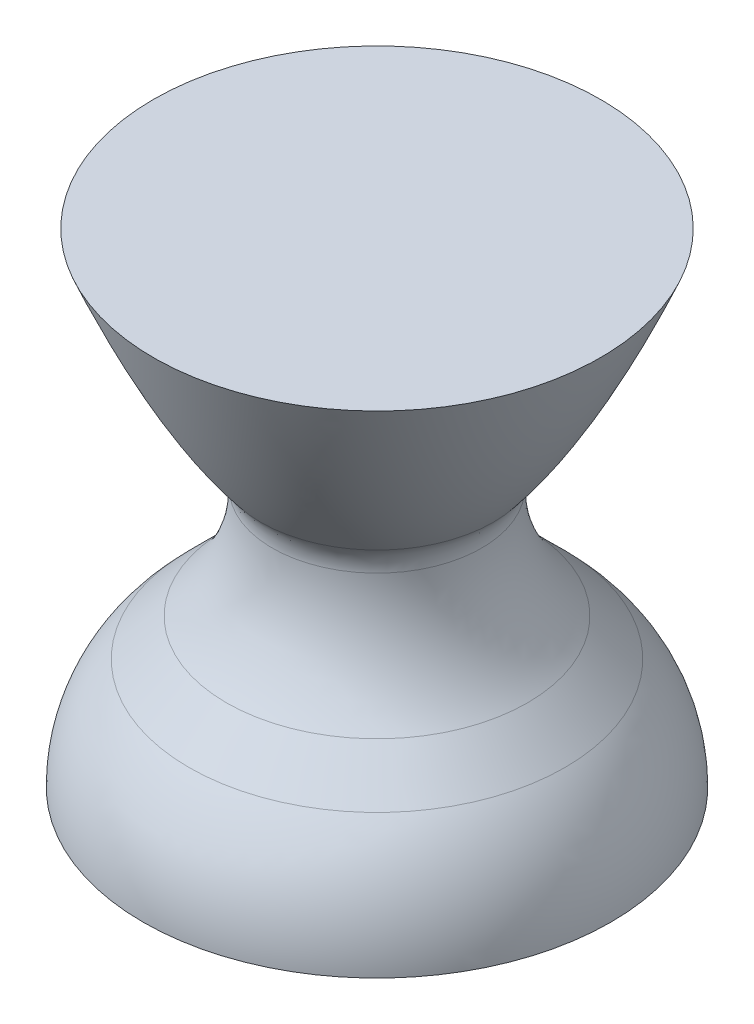
SolidWorks part; units mm, degrees
ref_plane "Front Plane" through (0, 0, 0) normal (0, 0, 1) x (1, 0, 0)
ref_plane "Top Plane" through (0, 0, 0) normal (0, 1, 0) x (1, 0, 0)
ref_plane "Right Plane" through (0, 0, 0) normal (1, 0, 0) x (0, 0, -1)
sketch "Sketch1" plane through (0, 0, 0) normal (0, 0, 1) x (1, 0, 0)
  line L0 (0, 61.1625) -> (0, -71.9343) construction
  line L1 (53.8816, -59.7274) -> (0, -59.7274)
  line L2 (51.5099, 51.7205) -> (0, 51.7205)
  line L3 (0, 51.7205) -> (0, -59.7274)
  spline S0 degree 2 poles (26.7954, 6.5095) (39.1527, 21.9803) (51.5099, 51.7205) knots 0 0 0 1 1 1 construction
  spline S1 degree 2 poles (26.7954, 6.5095) (39.1527, 21.9803) (51.5099, 51.7205) knots 0 0 0 1 1 1
  spline S2 degree 4 poles (24.127, -0.7178) (24.1261, -0.7017) (24.1244, -0.6737) (24.1211, -0.6545) (24.1152, -0.5165) (24.106, -0.4368) (24.0995, -0.1065) (24.0981, 0.0019) (24.1021, 0.2679) (24.1086, 0.4273) (24.1207, 0.647) (24.1416, 0.9017) (24.1753, 1.2028) (24.2266, 1.5423) (24.2907, 1.8813) (24.3673, 2.2166) (24.4564, 2.5495) (24.5579, 2.8784) (24.6717, 3.2036) (24.7973, 3.5239) (24.9354, 3.8399) (25.0842, 4.1496) (25.2461, 4.4551) (25.4166, 4.7516) (25.6026, 5.046) (25.7919, 5.3258) (26.0045, 5.611) (26.179, 5.8332) (26.3665, 6.0502) (26.5047, 6.2089) (26.7571, 6.4729) (26.8371, 6.5527) (27.1017, 6.8061) (27.1882, 6.8784) (27.2855, 6.9668) (27.3039, 6.9805) (27.3265, 7.0005) knots 0 0 0 0 0 0.005192 0.010384 0.020768 0.041536 0.082569 0.102427 0.122284 0.142142 0.162 0.201716 0.241431 0.281147 0.320863 0.360578 0.400294 0.44001 0.479725 0.519441 0.559156 0.598872 0.638588 0.678303 0.718019 0.757735 0.79745 0.837166 0.857024 0.876882 0.916597 0.958047 0.979024 0.989512 1 1 1 1 1 construction
  spline S3 degree 4 poles (24.0992, 0.0003) (24.0992, 0.0362) (24.0997, 0.1104) (24.1021, 0.2679) (24.1086, 0.4273) (24.1207, 0.647) (24.1416, 0.9017) (24.1753, 1.2028) (24.2266, 1.5423) (24.2907, 1.8813) (24.3673, 2.2166) (24.4564, 2.5495) (24.5579, 2.8784) (24.6717, 3.2036) (24.7973, 3.5239) (24.9354, 3.8399) (25.0842, 4.1496) (25.2461, 4.4551) (25.4166, 4.7516) (25.6026, 5.046) (25.7919, 5.3258) (26.0045, 5.611) (26.179, 5.8332) (26.3665, 6.0502) (26.5047, 6.2089) (26.6706, 6.3824) (26.7446, 6.4588) (26.7954, 6.5095) knots 0.082569 0.082569 0.082569 0.082569 0.082569 0.102427 0.122284 0.142142 0.162 0.201716 0.241431 0.281147 0.320863 0.360578 0.400294 0.44001 0.479725 0.519441 0.559156 0.598872 0.638588 0.678303 0.718019 0.757735 0.79745 0.837166 0.857024 0.876882 0.916597 0.916597 0.916597 0.916597 0.916597
  spline S4 degree 4 poles (24.2083, 2.8081) (24.2015, 2.7167) (24.1883, 2.5519) (24.1643, 2.1755) (24.1353, 1.6882) (24.115, 1.1019) (24.1031, 0.6557) (24.0989, 0.1105) (24.0989, -0.0998) (24.1021, -0.5429) (24.1084, -0.8239) (24.1179, -1.1945) (24.1305, -1.5132) (24.1463, -1.8617) (24.1653, -2.1934) (24.1929, -2.6178) (24.2324, -3.1218) (24.3034, -3.8797) (24.4232, -4.8862) (24.5996, -6.0564) (24.851, -7.3849) (25.1519, -8.7033) (25.5019, -10.0094) (25.9005, -11.3015) (26.3471, -12.5778) (26.8411, -13.8366) (27.3818, -15.0759) (27.9686, -16.2943) (28.6003, -17.4897) (29.2767, -18.661) (29.9956, -19.8055) (30.7581, -20.9236) (31.4593, -21.8741) (32.0889, -22.6732) (32.6242, -23.3201) (33.0724, -23.8397) (33.5086, -24.3295) (33.9359, -24.7882) (34.2457, -25.1136) (34.6122, -25.4858) (34.7662, -25.6397) (35.151, -26.0186) (35.4777, -26.3285) (35.9051, -26.7271) (36.2397, -27.0241) (36.5193, -27.2706) (36.6466, -27.3797) (36.7149, -27.4386) (36.7497, -27.4684) knots 0 0 0 0 0 0.010393 0.020785 0.041571 0.062104 0.072371 0.082638 0.092575 0.102512 0.112449 0.122387 0.132324 0.142261 0.152198 0.162135 0.18201 0.201884 0.241633 0.281382 0.32113 0.360879 0.400628 0.440377 0.480126 0.519874 0.559623 0.599372 0.639121 0.67887 0.718618 0.758367 0.798116 0.81799 0.837865 0.857739 0.877613 0.897488 0.907425 0.917362 0.927629 0.937896 0.958429 0.979215 0.989607 0.994804 1 1 1 1 1 construction
  spline S5 degree 4 poles (24.0992, 0.0003) (24.0992, -0.0703) (24.0997, -0.2133) (24.1021, -0.5429) (24.1084, -0.8239) (24.1179, -1.1945) (24.1305, -1.5132) (24.1463, -1.8617) (24.1653, -2.1934) (24.1929, -2.6178) (24.2324, -3.1218) (24.3034, -3.8797) (24.4232, -4.8862) (24.5996, -6.0564) (24.851, -7.3849) (25.1519, -8.7033) (25.5019, -10.0094) (25.9005, -11.3015) (26.3471, -12.5778) (26.8411, -13.8366) (27.3818, -15.0759) (27.9686, -16.2943) (28.6003, -17.4897) (29.2767, -18.661) (29.9956, -19.8055) (30.7581, -20.9236) (31.4593, -21.8741) (32.0889, -22.6732) (32.6242, -23.3201) (33.0724, -23.8397) (33.5086, -24.3295) (33.9359, -24.7882) (34.2457, -25.1136) (34.537, -25.4094) (34.6365, -25.5097) (34.6864, -25.5595) knots 0.082638 0.082638 0.082638 0.082638 0.082638 0.092575 0.102512 0.112449 0.122387 0.132324 0.142261 0.152198 0.162135 0.18201 0.201884 0.241633 0.281382 0.32113 0.360879 0.400628 0.440377 0.480126 0.519874 0.559623 0.599372 0.639121 0.67887 0.718618 0.758367 0.798116 0.81799 0.837865 0.857739 0.877613 0.897488 0.907425 0.917362 0.917362 0.917362 0.917362 0.917362
  spline S6 degree 1 poles (34.6864, -25.5595) (43.294, -34.1672) knots 0 0 1 1 construction
  spline S7 degree 1 poles (34.6864, -25.5595) (43.294, -34.1672) knots 0 0 1 1
  spline S8 degree 4 poles (53.7725, -62.5351) (53.7793, -62.4463) (53.7925, -62.2736) (53.8105, -62.0015) (53.8311, -61.6598) (53.8481, -61.292) (53.8617, -60.9657) (53.8718, -60.5751) (53.8786, -60.2938) (53.8819, -59.8331) (53.8819, -59.6303) (53.8787, -59.1814) (53.8724, -58.9047) (53.8629, -58.5325) (53.8503, -58.2127) (53.8305, -57.7815) (53.8005, -57.2808) (53.7563, -56.6879) (53.6774, -55.8484) (53.5775, -55.0081) (53.4568, -54.1723) (53.2869, -53.1723) (53.0922, -52.1773) (52.8665, -51.1884) (52.6101, -50.2074) (52.3294, -49.233) (52.0245, -48.2659) (51.6337, -47.149) (51.1396, -45.8903) (50.5989, -44.6509) (50.0122, -43.4326) (49.3802, -42.237) (48.7042, -41.066) (47.9846, -39.9209) (47.2232, -38.804) (46.52, -37.8513) (45.8937, -37.0556) (45.3529, -36.4033) (44.9152, -35.8941) (44.5149, -35.4469) (44.1816, -35.0845) (43.874, -34.7602) (43.6742, -34.5514) (43.3654, -34.2381) (43.216, -34.0888) (42.8278, -33.7065) (42.5042, -33.3996) (42.0742, -32.9985) (41.7413, -32.7032) (41.4608, -32.4558) (41.3339, -32.3471) (41.2655, -32.2882) (41.2306, -32.2582) knots 0 0 0 0 0 0.010393 0.020785 0.031178 0.041571 0.051838 0.062104 0.072371 0.082638 0.092575 0.102512 0.112449 0.122387 0.132324 0.142261 0.162135 0.18201 0.201884 0.241633 0.261507 0.281382 0.32113 0.360879 0.380754 0.400628 0.440377 0.480126 0.519874 0.559623 0.599372 0.639121 0.67887 0.718618 0.758367 0.798116 0.81799 0.837865 0.857739 0.877613 0.887551 0.897488 0.907425 0.917362 0.927629 0.937896 0.958429 0.979215 0.989607 0.994804 1 1 1 1 1 construction
  spline S9 degree 4 poles (53.8816, -59.7274) (53.8816, -59.6569) (53.8811, -59.5153) (53.8787, -59.1814) (53.8724, -58.9047) (53.8629, -58.5325) (53.8503, -58.2127) (53.8305, -57.7815) (53.8005, -57.2808) (53.7563, -56.6879) (53.6774, -55.8484) (53.5775, -55.0081) (53.4568, -54.1723) (53.2869, -53.1723) (53.0922, -52.1773) (52.8665, -51.1884) (52.6101, -50.2074) (52.3294, -49.233) (52.0245, -48.2659) (51.6337, -47.149) (51.1396, -45.8903) (50.5989, -44.6509) (50.0122, -43.4326) (49.3802, -42.237) (48.7042, -41.066) (47.9846, -39.9209) (47.2232, -38.804) (46.52, -37.8513) (45.8937, -37.0556) (45.3529, -36.4033) (44.9152, -35.8941) (44.5149, -35.4469) (44.1816, -35.0845) (43.874, -34.7602) (43.6742, -34.5514) (43.4445, -34.3184) (43.3439, -34.217) (43.294, -34.1672) knots 0.082638 0.082638 0.082638 0.082638 0.082638 0.092575 0.102512 0.112449 0.122387 0.132324 0.142261 0.162135 0.18201 0.201884 0.241633 0.261507 0.281382 0.32113 0.360879 0.380754 0.400628 0.440377 0.480126 0.519874 0.559623 0.599372 0.639121 0.67887 0.718618 0.758367 0.798116 0.81799 0.837865 0.857739 0.877613 0.887551 0.897488 0.907425 0.917362 0.917362 0.917362 0.917362 0.917362
  dimension "D1" = 24.0992
revolve "Revolve1" add sketch "Sketch1" angle 360 about L0
